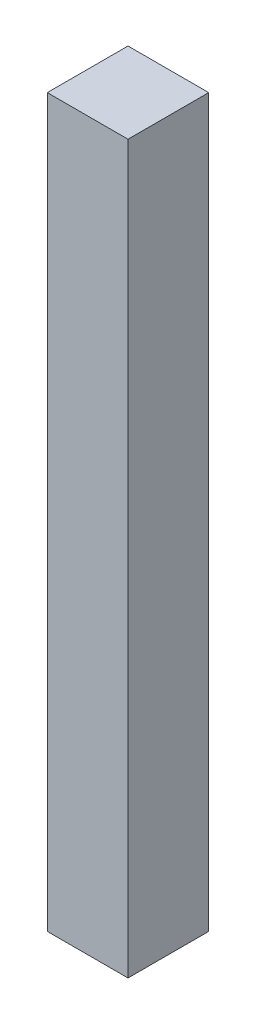
SolidWorks part; units mm, degrees
ref_plane "Front Plane" through (0, 0, 0) normal (0, 0, 1) x (1, 0, 0)
ref_plane "Top Plane" through (0, 0, 0) normal (0, 1, 0) x (1, 0, 0)
ref_plane "Right Plane" through (0, 0, 0) normal (1, 0, 0) x (0, 0, -1)
sketch "Sketch1" plane through (0, 0, 0) normal (0, 1, 0) x (1, 0, 0)
  line L1 (-50.8, -50.8) -> (50.8, -50.8)
  line L2 (-50.8, -50.8) -> (-50.8, 50.8)
  line L3 (-50.8, 50.8) -> (50.8, 50.8)
  line L4 (50.8, -50.8) -> (50.8, 50.8)
  line L5 (-50.8, -50.8) -> (50.8, 50.8) construction
  line L6 (-50.8, 50.8) -> (50.8, -50.8) construction
  point P0 (0, 0)
  dimension "D1" = 101.6
  dimension "D2" = 101.6
extrude "Boss-Extrude1" add sketch "Sketch1" along normal blind 914.4
